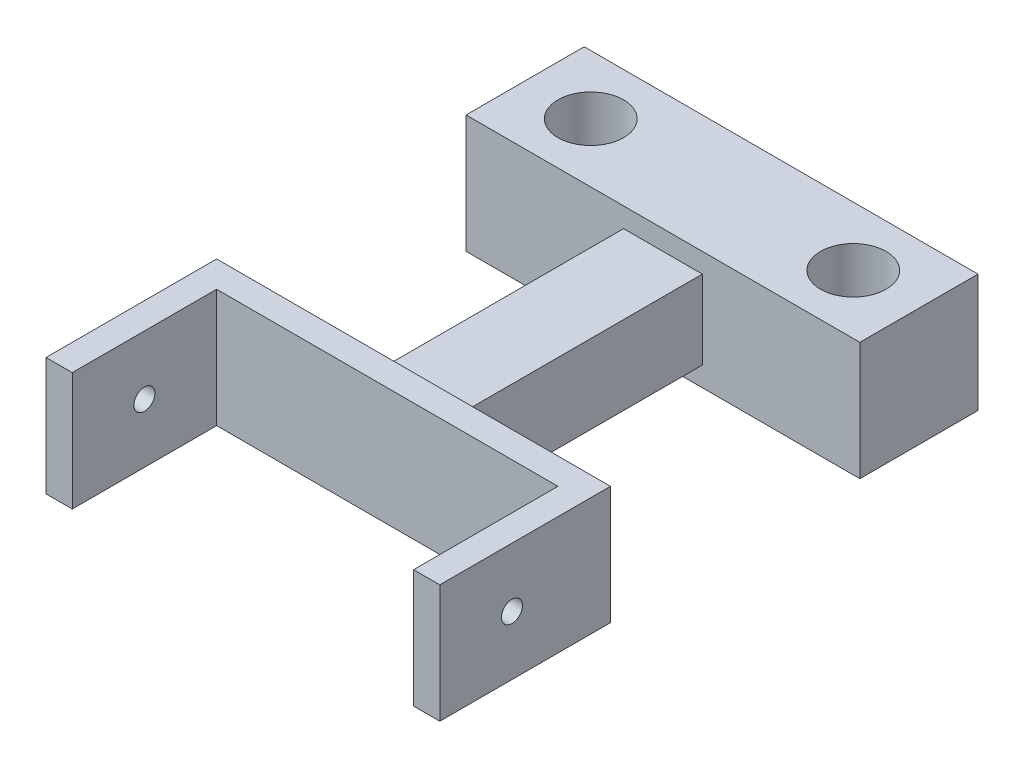
SolidWorks part; units mm, degrees
ref_plane "前视基准面" through (0, 0, 0) normal (0, 0, 1) x (1, 0, 0)
ref_plane "上视基准面" through (0, 0, 0) normal (0, 1, 0) x (1, 0, 0)
ref_plane "右视基准面" through (0, 0, 0) normal (1, 0, 0) x (0, 0, -1)
other "Configuration Table"
sketch "草图1" plane through (0, 0, 0) normal (0, 0, 1) x (1, 0, 0)
  line L1 (-75, 22.5) -> (75, 22.5)
  line L2 (-75, 22.5) -> (-75, -22.5)
  line L3 (-75, -22.5) -> (75, -22.5)
  line L4 (75, 22.5) -> (75, -22.5)
  line L5 (-75, 22.5) -> (75, -22.5) construction
  line L6 (-75, -22.5) -> (75, 22.5) construction
  point P0 (0, 0)
  dimension "D1" = 150
  dimension "D2" = 45
extrude "凸台-拉伸1" add sketch "草图1" against normal blind 45
sketch "草图2" plane through (0, 0, 0) normal (0, 1, 0) x (1, 0, 0)
  line L0 (-75, 22.5) -> (75, 22.5) construction
  line L1 (-75, 45) -> (-75, 0) construction
  line L2 (75, 45) -> (75, 0) construction
  line L3 (-50, 22.5) -> (50, 22.5) construction
  circle A0 centre (-50, 22.5) radius 12.5
  circle A1 centre (50, 22.5) radius 12.5
  point P8 (0, 22.5)
  point P9 (0, 22.5)
  dimension "D2" = 25
  dimension "D3" = 25
  dimension "D1" = 100
extrude "切除-拉伸1" cut sketch "草图2" against normal through all both and the other way through all
sketch "草图3" plane through (0, 0, 0) normal (0, 0, 1) x (1, 0, 0)
  line L1 (-15, 15) -> (15, 15)
  line L2 (-15, 15) -> (-15, -15)
  line L3 (-15, -15) -> (15, -15)
  line L4 (15, 15) -> (15, -15)
  line L5 (-15, 15) -> (15, -15) construction
  line L6 (-15, -15) -> (15, 15) construction
  point P0 (0, 0)
  dimension "D1" = 30
  dimension "D2" = 30
extrude "凸台-拉伸2" add sketch "草图3" along normal blind 95
sketch "草图4" plane through (0, 0, 0) normal (0, 1, 0) x (1, 0, 0)
  line L0 (-75, -95) -> (75, -95)
  line L1 (75, -95) -> (75, -160)
  line L2 (75, -160) -> (65, -160)
  line L3 (65, -160) -> (65, -105)
  line L4 (65, -105) -> (-65, -105)
  line L5 (-65, -105) -> (-65, -160)
  line L6 (-65, -160) -> (-75, -160)
  line L7 (-75, -160) -> (-75, -95)
  dimension "D1" = 65
  dimension "D2" = 10
  dimension "D3" = 10
  dimension "D4" = 10
extrude "凸台-拉伸3" add sketch "草图4" along normal mid plane 45
sketch "草图5" plane through (0, 0, 0) normal (1, 0, 0) x (0, 0, -1)
  line L0 (-160, 22.5) -> (-105, -22.5) construction
  line L2 (-105, 22.5) -> (-160, -22.5) construction
  circle A0 centre (-132.5, 0) radius 4
  dimension "D1" = 8
extrude "切除-拉伸2" cut sketch "草图5" against normal through all both and the other way through all
